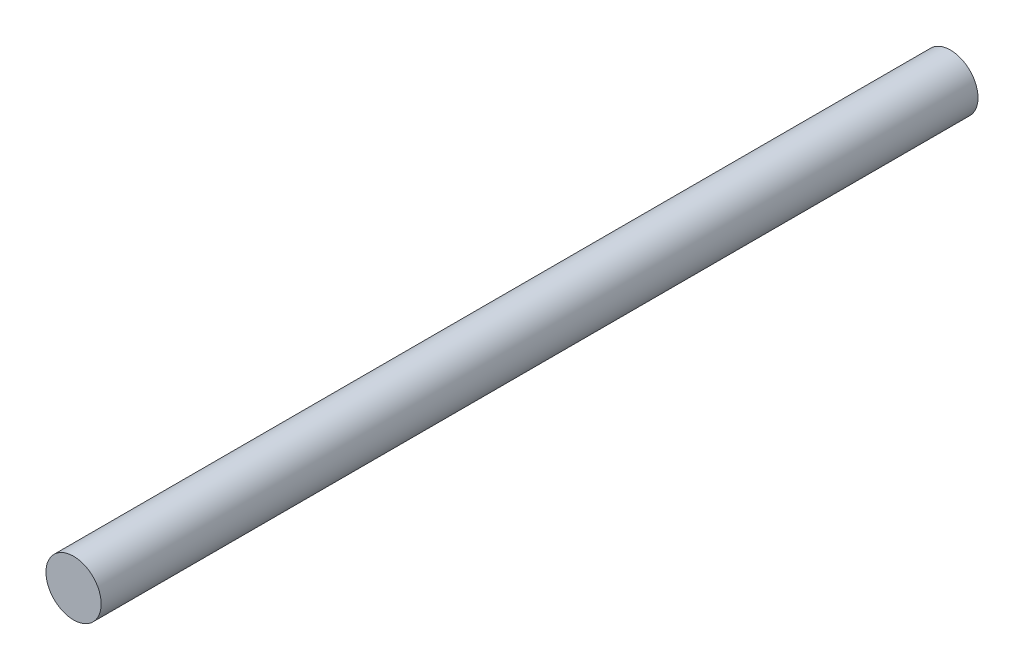
SolidWorks part; units mm, degrees
ref_plane "Front Plane" through (0, 0, 0) normal (0, 0, 1) x (1, 0, 0)
ref_plane "Top Plane" through (0, 0, 0) normal (0, 1, 0) x (1, 0, 0)
ref_plane "Right Plane" through (0, 0, 0) normal (1, 0, 0) x (0, 0, -1)
sketch "Sketch1" plane through (0, 0, 0) normal (0, 0, 1) x (1, 0, 0)
  circle A0 centre (0, 0) radius 4
extrude "Boss-Extrude1" add sketch "Sketch1" along normal blind 127
